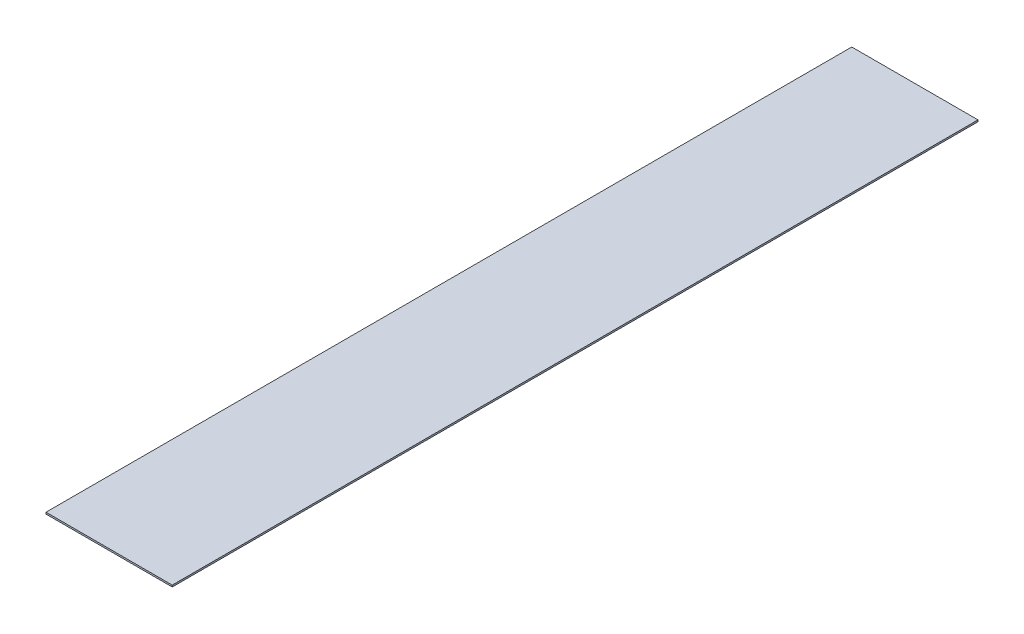
SolidWorks part; units mm, degrees
material "concrete"
ref_plane "Front Plane" through (0, 0, 0) normal (0, 0, 1) x (1, 0, 0)
ref_plane "Top Plane" through (0, 0, 0) normal (0, 1, 0) x (1, 0, 0)
ref_plane "Right Plane" through (0, 0, 0) normal (1, 0, 0) x (0, 0, -1)
sketch "Sketch2" plane through (0, 0, 0) normal (0, 1, 0) x (1, 0, 0)
  line L1 (-1880, 12000) -> (1880, 12000)
  line L2 (-1880, 12000) -> (-1880, -12000)
  line L3 (-1880, -12000) -> (1880, -12000)
  line L4 (1880, 12000) -> (1880, -12000)
  line L5 (-1880, 12000) -> (1880, -12000) construction
  line L6 (-1880, -12000) -> (1880, 12000) construction
  point P0 (0, 0)
  dimension "D1" = 3760
  dimension "D2" = 24000
extrude "Boss-Extrude1" add sketch "Sketch2" along normal blind 50
